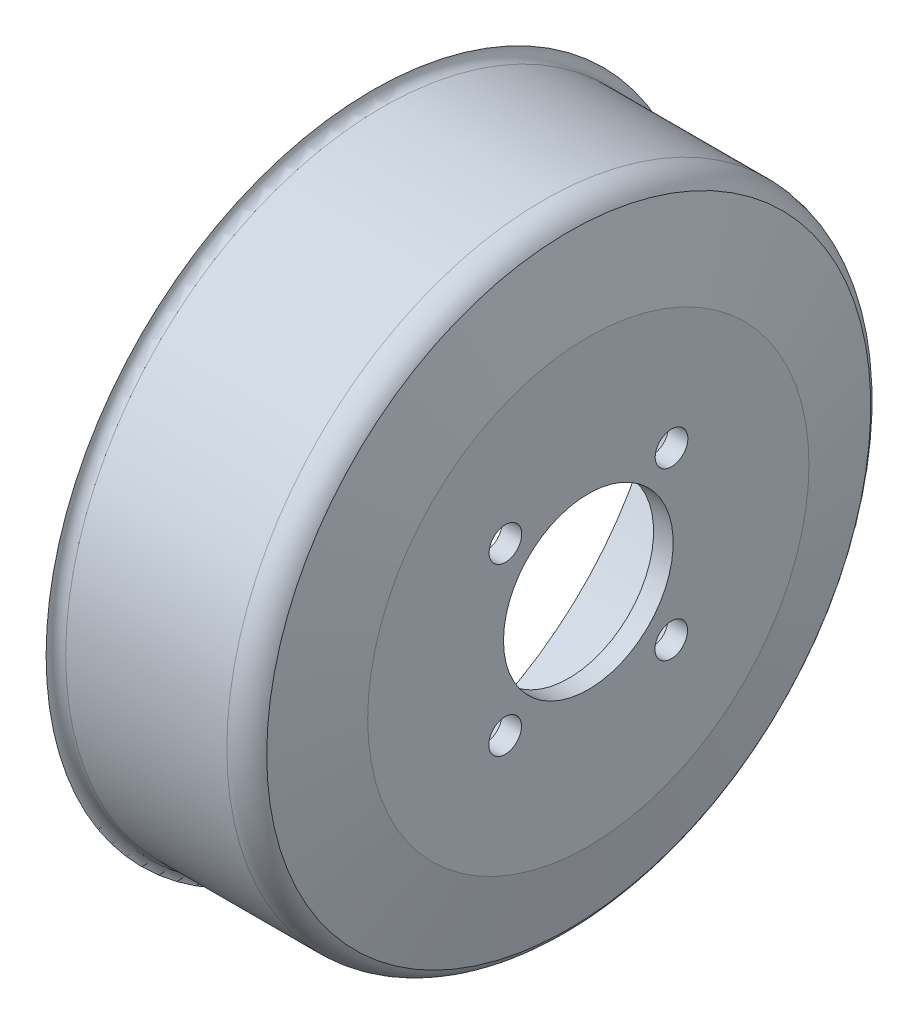
SolidWorks part; units mm, degrees
ref_plane "Front Plane" through (0, 0, 0) normal (0, 0, 1) x (1, 0, 0)
ref_plane "Top Plane" through (0, 0, 0) normal (0, 1, 0) x (1, 0, 0)
ref_plane "Right Plane" through (0, 0, 0) normal (1, 0, 0) x (0, 0, -1)
sketch "Sketch1" plane through (0, 0, 0) normal (0, 0, 1) x (1, 0, 0)
  line L0 (-30.7282, 0) -> (41.9539, 0) construction
  line L1 (55, 0) -> (-55, 0) construction
  line L3 (15, 97) -> (60.316, 97)
  line L4 (12, 91) -> (12, 100)
  line L5 (60.316, 97) -> (64.3824, 97)
  line L8 (12, 91) -> (63.8183, 91)
  line L10 (12, 91) -> (69.546, 91) construction
  line L15 (72.1521, 26) -> (78.1521, 26)
  line L18 (12, 97) -> (69.546, 97) construction
  line L21 (72.1521, 26) -> (72.1521, 67.6134)
  line L22 (78.1521, 26) -> (78.1521, 67.6134)
  line L23 (66.4082, 89.473) -> (72.1521, 67.6134)
  line L24 (72.1521, 92.5423) -> (78.1521, 67.6134)
  arc A1 (15, 97) -> (12, 100) centre (15, 100) cw
  arc A3 (66.4082, 89.473) -> (63.8183, 91) centre (63.8183, 88.0402) ccw
  arc A4 (72.1521, 92.5423) -> (64.3824, 97) centre (64.3824, 88) ccw
  dimension "D1" = 6
  dimension "D4" = 26
  dimension "D6" = 100
  dimension "D7" = 6
revolve "Revolve1" add sketch "Sketch1" angle 360 about L0
sketch "Sketch2" plane through (78.1521, 0, 0) normal (1, 0, 0) x (0, 0, -1)
  circle A0 centre (0, 0) radius 36 construction
  circle A1 centre (-25.4125, 25.4991) radius 5
  circle A2 centre (25.4975, 25.4141) radius 5
  circle A3 centre (25.4158, -25.4959) radius 5
  circle A4 centre (-25.4942, -25.4175) radius 5
  point P13 (-23.6925, -20.8022)
  point P14 (25.5096, -21.7177)
  dimension "D1" = 72
  dimension "D2" = 10
  dimension "D3" = 50.91
  dimension "D4" = 50.91
  dimension "D5" = 50.91
extrude "Cut-Extrude1" cut sketch "Sketch2" against normal blind 10 contours A1 | A2 | A3 | A4
